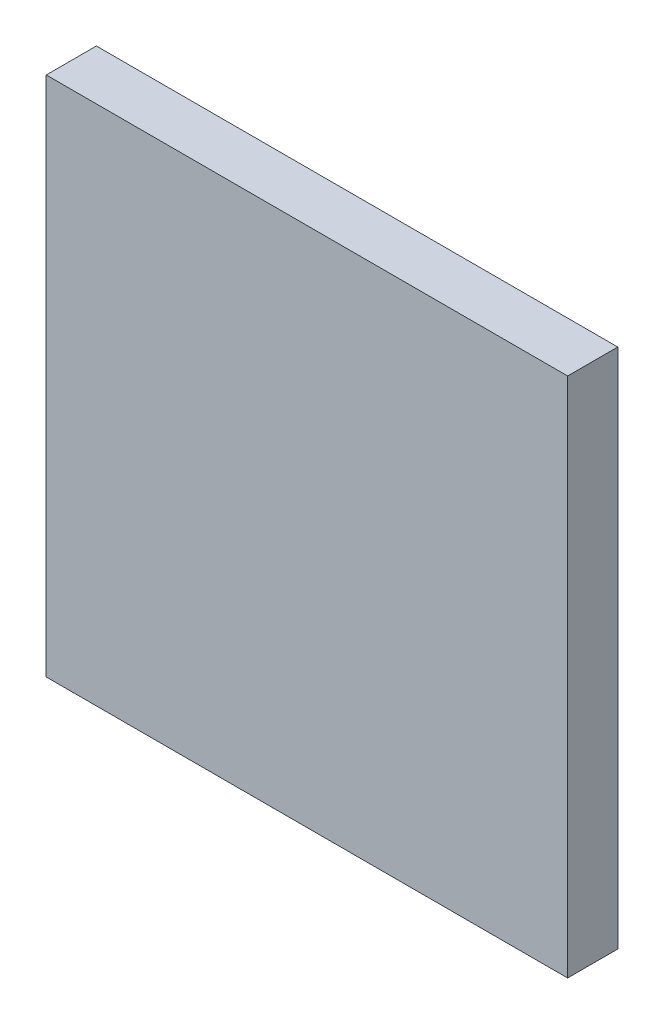
SolidWorks part; units mm, degrees
other "Marquage2"
sketch "Esquisse4" plane through (-13, -13, 1.25) normal (0, 0, 1) x (1, 0, 0)
other "Objet de détail1"
other "Marquage3"
sketch "Esquisse5"
ref_plane "Plan de face" through (0, 0, 0) normal (0, 0, 1) x (1, 0, 0)
ref_plane "Plan de dessus" through (0, 0, 0) normal (0, 1, 0) x (1, 0, 0)
ref_plane "Plan de droite" through (0, 0, 0) normal (1, 0, 0) x (0, 0, -1)
sketch "Esquisse1" plane through (0, 0, 0) normal (0, 0, 1) x (1, 0, 0)
  line L1 (-13, -13) -> (13, -13)
  line L2 (-13, -13) -> (-13, 13)
  line L3 (-13, 13) -> (13, 13)
  line L4 (13, -13) -> (13, 13)
  line L5 (-13, -13) -> (13, 13) construction
  line L6 (-13, 13) -> (13, -13) construction
  point P0 (0, 0)
  point P8 (0, 0)
  dimension "D1" = 26
  dimension "D2" = 26
extrude "Boss.-Extru.1" add sketch "Esquisse1" along normal mid plane 2.5
sketch "Esquisse2" plane through (0, 0, 1.25) normal (0, 0, 1) x (1, 0, 0)
  point P0 (0, 0)
